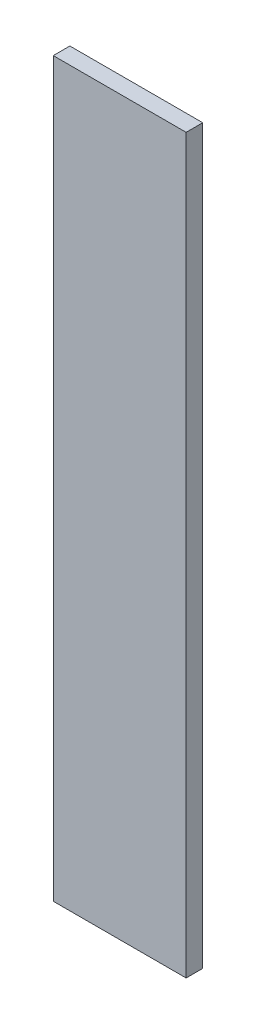
SolidWorks part; units mm, degrees
ref_plane "Front Plane" through (0, 0, 0) normal (0, 0, 1) x (1, 0, 0)
ref_plane "Top Plane" through (0, 0, 0) normal (0, 1, 0) x (1, 0, 0)
ref_plane "Right Plane" through (0, 0, 0) normal (1, 0, 0) x (0, 0, -1)
sketch "Sketch1" plane through (0, 0, 0) normal (0, 0, 1) x (1, 0, 0)
  line L1 (0, 0) -> (25.4, 0)
  line L2 (0, 0) -> (0, 140)
  line L3 (0, 140) -> (25.4, 140)
  line L4 (25.4, 0) -> (25.4, 140)
  dimension "D1" = 25.4
  dimension "D2" = 140
extrude "Boss-Extrude1" add sketch "Sketch1" along normal blind 3.175
